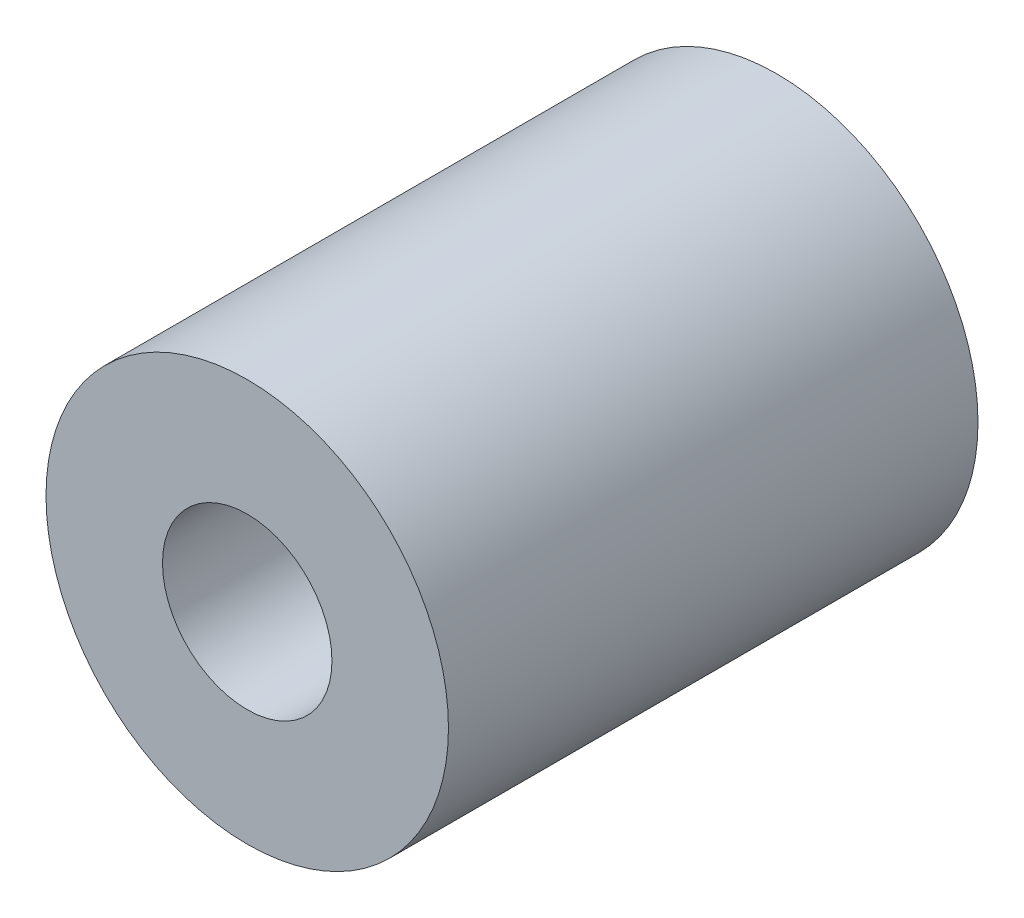
SolidWorks part; units mm, degrees
ref_plane "Front" through (0, 0, 0) normal (0, 0, 1) x (1, 0, 0)
ref_plane "Top" through (0, 0, 0) normal (0, 1, 0) x (1, 0, 0)
ref_plane "Right" through (0, 0, 0) normal (1, 0, 0) x (0, 0, -1)
sketch "草图1" plane through (0, 0, 0) normal (0, 0, 1) x (1, 0, 0)
  circle A0 centre (0, 0) radius 9.5
  dimension "D1" = 19
extrude "凸台-拉伸1" add sketch "草图1" along normal blind 25
sketch "草图2" plane through (0, 0, 25) normal (0, 0, 1) x (1, 0, 0)
  circle A0 centre (0, 0) radius 4
  dimension "D1" = 8
extrude "切除-拉伸1" cut sketch "草图2" against normal blind 12.5
sketch "草图3" plane through (0, 0, 0) normal (0, 0, -1) x (-1, 0, 0)
  circle A0 centre (0, 0) radius 3
  dimension "D1" = 6
extrude "切除-拉伸2" cut sketch "草图3" against normal blind 12.5
